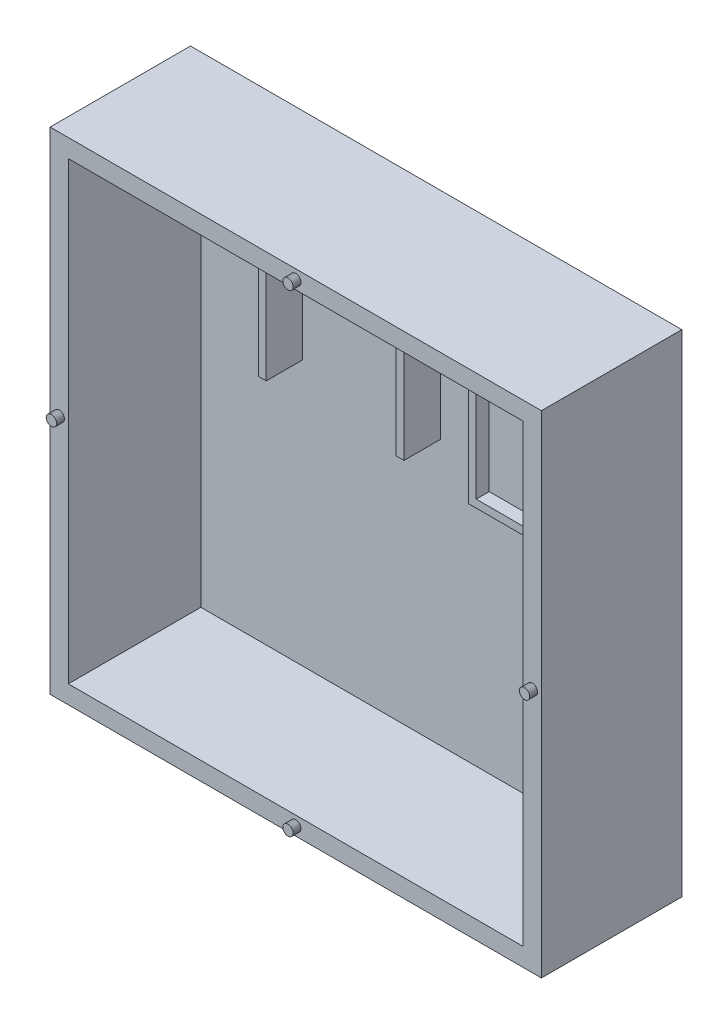
SolidWorks part; units mm, degrees
ref_plane "Front Plane" through (0, 0, 0) normal (0, 0, 1) x (1, 0, 0)
ref_plane "Top Plane" through (0, 0, 0) normal (0, 1, 0) x (1, 0, 0)
ref_plane "Right Plane" through (0, 0, 0) normal (1, 0, 0) x (0, 0, -1)
ref_plane "Plane1" through (0, 0, 0) normal (0, 0, -1) x (-1, 0, 0)
sketch "Sketch1" plane through (0, 0, 0) normal (0, 0, -1) x (-1, 0, 0)
  line L0 (-189, 189) -> (-189, 0)
  line L1 (-189, 0) -> (0, 0)
  line L2 (0, 0) -> (0, 189)
  line L3 (0, 189) -> (-189, 189)
extrude "Boss-Extrude1" add sketch "Sketch1" against normal blind 54
sketch "Sketch2" plane through (0, 0, 54) normal (0, 0, 1) x (1, 0, 0)
  line L0 (3.1527, 96.4696) -> (3.5, 96.5)
  line L1 (3.5, 96.5) -> (3.8473, 96.4696)
  line L2 (3.8473, 96.4696) -> (4.184, 96.3794)
  line L3 (4.184, 96.3794) -> (4.5, 96.232)
  line L4 (4.5, 96.232) -> (4.7856, 96.0321)
  line L5 (4.7856, 96.0321) -> (5.0321, 95.7856)
  line L6 (5.0321, 95.7856) -> (5.2321, 95.5)
  line L7 (5.2321, 95.5) -> (5.3794, 95.184)
  line L8 (5.3794, 95.184) -> (5.4696, 94.8473)
  line L9 (5.4696, 94.8473) -> (5.5, 94.5)
  line L10 (5.5, 94.5) -> (5.4696, 94.1527)
  line L11 (5.4696, 94.1527) -> (5.3794, 93.816)
  line L12 (5.3794, 93.816) -> (5.2321, 93.5)
  line L13 (5.2321, 93.5) -> (5.0321, 93.2144)
  line L14 (5.0321, 93.2144) -> (4.7856, 92.9679)
  line L15 (4.7856, 92.9679) -> (4.5, 92.7679)
  line L16 (4.5, 92.7679) -> (4.184, 92.6206)
  line L17 (4.184, 92.6206) -> (3.8473, 92.5304)
  line L18 (3.8473, 92.5304) -> (3.5, 92.5)
  line L19 (3.5, 92.5) -> (3.1527, 92.5304)
  line L20 (3.1527, 92.5304) -> (2.816, 92.6206)
  line L21 (2.816, 92.6206) -> (2.5, 92.7679)
  line L22 (2.5, 92.7679) -> (2.2144, 92.9679)
  line L23 (2.2144, 92.9679) -> (1.9679, 93.2144)
  line L24 (1.9679, 93.2144) -> (1.7679, 93.5)
  line L25 (1.7679, 93.5) -> (1.6206, 93.816)
  line L26 (1.6206, 93.816) -> (1.5304, 94.1527)
  line L27 (1.5304, 94.1527) -> (1.5, 94.5)
  line L28 (1.5, 94.5) -> (1.5304, 94.8473)
  line L29 (1.5304, 94.8473) -> (1.6206, 95.184)
  line L30 (1.6206, 95.184) -> (1.7679, 95.5)
  line L31 (1.7679, 95.5) -> (1.9679, 95.7856)
  line L32 (1.9679, 95.7856) -> (2.2144, 96.0321)
  line L33 (2.2144, 96.0321) -> (2.5, 96.232)
  line L34 (2.5, 96.232) -> (2.816, 96.3794)
  line L35 (2.816, 96.3794) -> (3.1527, 96.4696)
extrude "Boss-Extrude2" add sketch "Sketch2" along normal blind 3
sketch "Sketch3" plane through (0, 0, 54) normal (0, 0, 1) x (1, 0, 0)
  line L0 (96.0321, 184.2144) -> (95.7856, 183.9679)
  line L1 (95.7856, 183.9679) -> (95.5, 183.7679)
  line L2 (95.5, 183.7679) -> (95.184, 183.6206)
  line L3 (95.184, 183.6206) -> (94.8473, 183.5304)
  line L4 (94.8473, 183.5304) -> (94.5, 183.5)
  line L5 (94.5, 183.5) -> (94.1527, 183.5304)
  line L6 (94.1527, 183.5304) -> (93.816, 183.6206)
  line L7 (93.816, 183.6206) -> (93.5, 183.7679)
  line L8 (93.5, 183.7679) -> (93.2144, 183.9679)
  line L9 (93.2144, 183.9679) -> (92.9679, 184.2144)
  line L10 (92.9679, 184.2144) -> (92.768, 184.5)
  line L11 (92.768, 184.5) -> (92.6206, 184.816)
  line L12 (92.6206, 184.816) -> (92.5304, 185.1527)
  line L13 (92.5304, 185.1527) -> (92.5, 185.5)
  line L14 (92.5, 185.5) -> (92.5304, 185.8473)
  line L15 (92.5304, 185.8473) -> (92.6206, 186.184)
  line L16 (92.6206, 186.184) -> (92.768, 186.5)
  line L17 (92.768, 186.5) -> (92.9679, 186.7856)
  line L18 (92.9679, 186.7856) -> (93.2144, 187.0321)
  line L19 (93.2144, 187.0321) -> (93.5, 187.232)
  line L20 (93.5, 187.232) -> (93.816, 187.3794)
  line L21 (93.816, 187.3794) -> (94.1527, 187.4696)
  line L22 (94.1527, 187.4696) -> (94.5, 187.5)
  line L23 (94.5, 187.5) -> (94.8473, 187.4696)
  line L24 (94.8473, 187.4696) -> (95.184, 187.3794)
  line L25 (95.184, 187.3794) -> (95.5, 187.232)
  line L26 (95.5, 187.232) -> (95.7856, 187.0321)
  line L27 (95.7856, 187.0321) -> (96.0321, 186.7856)
  line L28 (96.0321, 186.7856) -> (96.2321, 186.5)
  line L29 (96.2321, 186.5) -> (96.3794, 186.184)
  line L30 (96.3794, 186.184) -> (96.4696, 185.8473)
  line L31 (96.4696, 185.8473) -> (96.5, 185.5)
  line L32 (96.5, 185.5) -> (96.4696, 185.1527)
  line L33 (96.4696, 185.1527) -> (96.3794, 184.816)
  line L34 (96.3794, 184.816) -> (96.2321, 184.5)
  line L35 (96.2321, 184.5) -> (96.0321, 184.2144)
extrude "Boss-Extrude3" add sketch "Sketch3" along normal blind 3
sketch "Sketch4" plane through (0, 0, 54) normal (0, 0, 1) x (1, 0, 0)
  line L0 (185.8473, 92.5304) -> (185.5, 92.5)
  line L1 (185.5, 92.5) -> (185.1527, 92.5304)
  line L2 (185.1527, 92.5304) -> (184.816, 92.6206)
  line L3 (184.816, 92.6206) -> (184.5, 92.7679)
  line L4 (184.5, 92.7679) -> (184.2144, 92.9679)
  line L5 (184.2144, 92.9679) -> (183.9679, 93.2144)
  line L6 (183.9679, 93.2144) -> (183.768, 93.5)
  line L7 (183.768, 93.5) -> (183.6206, 93.816)
  line L8 (183.6206, 93.816) -> (183.5304, 94.1527)
  line L9 (183.5304, 94.1527) -> (183.5, 94.5)
  line L10 (183.5, 94.5) -> (183.5304, 94.8473)
  line L11 (183.5304, 94.8473) -> (183.6206, 95.184)
  line L12 (183.6206, 95.184) -> (183.768, 95.5)
  line L13 (183.768, 95.5) -> (183.9679, 95.7856)
  line L14 (183.9679, 95.7856) -> (184.2144, 96.0321)
  line L15 (184.2144, 96.0321) -> (184.5, 96.232)
  line L16 (184.5, 96.232) -> (184.816, 96.3794)
  line L17 (184.816, 96.3794) -> (185.1527, 96.4696)
  line L18 (185.1527, 96.4696) -> (185.5, 96.5)
  line L19 (185.5, 96.5) -> (185.8473, 96.4696)
  line L20 (185.8473, 96.4696) -> (186.184, 96.3794)
  line L21 (186.184, 96.3794) -> (186.5, 96.232)
  line L22 (186.5, 96.232) -> (186.7856, 96.0321)
  line L23 (186.7856, 96.0321) -> (187.0321, 95.7856)
  line L24 (187.0321, 95.7856) -> (187.2321, 95.5)
  line L25 (187.2321, 95.5) -> (187.3794, 95.184)
  line L26 (187.3794, 95.184) -> (187.4696, 94.8473)
  line L27 (187.4696, 94.8473) -> (187.5, 94.5)
  line L28 (187.5, 94.5) -> (187.4696, 94.1527)
  line L29 (187.4696, 94.1527) -> (187.3794, 93.816)
  line L30 (187.3794, 93.816) -> (187.2321, 93.5)
  line L31 (187.2321, 93.5) -> (187.0321, 93.2144)
  line L32 (187.0321, 93.2144) -> (186.7856, 92.9679)
  line L33 (186.7856, 92.9679) -> (186.5, 92.7679)
  line L34 (186.5, 92.7679) -> (186.184, 92.6206)
  line L35 (186.184, 92.6206) -> (185.8473, 92.5304)
extrude "Boss-Extrude4" add sketch "Sketch4" along normal blind 3
sketch "Sketch5" plane through (0, 0, 54) normal (0, 0, 1) x (1, 0, 0)
  line L0 (92.9679, 2.2144) -> (92.768, 2.5)
  line L1 (92.768, 2.5) -> (92.6206, 2.816)
  line L2 (92.6206, 2.816) -> (92.5304, 3.1527)
  line L3 (92.5304, 3.1527) -> (92.5, 3.5)
  line L4 (92.5, 3.5) -> (92.5304, 3.8473)
  line L5 (92.5304, 3.8473) -> (92.6206, 4.184)
  line L6 (92.6206, 4.184) -> (92.768, 4.5)
  line L7 (92.768, 4.5) -> (92.9679, 4.7856)
  line L8 (92.9679, 4.7856) -> (93.2144, 5.0321)
  line L9 (93.2144, 5.0321) -> (93.5, 5.2321)
  line L10 (93.5, 5.2321) -> (93.816, 5.3794)
  line L11 (93.816, 5.3794) -> (94.1527, 5.4696)
  line L12 (94.1527, 5.4696) -> (94.5, 5.5)
  line L13 (94.5, 5.5) -> (94.8473, 5.4696)
  line L14 (94.8473, 5.4696) -> (95.184, 5.3794)
  line L15 (95.184, 5.3794) -> (95.5, 5.2321)
  line L16 (95.5, 5.2321) -> (95.7856, 5.0321)
  line L17 (95.7856, 5.0321) -> (96.0321, 4.7856)
  line L18 (96.0321, 4.7856) -> (96.2321, 4.5)
  line L19 (96.2321, 4.5) -> (96.3794, 4.184)
  line L20 (96.3794, 4.184) -> (96.4696, 3.8473)
  line L21 (96.4696, 3.8473) -> (96.5, 3.5)
  line L22 (96.5, 3.5) -> (96.4696, 3.1527)
  line L23 (96.4696, 3.1527) -> (96.3794, 2.816)
  line L24 (96.3794, 2.816) -> (96.2321, 2.5)
  line L25 (96.2321, 2.5) -> (96.0321, 2.2144)
  line L26 (96.0321, 2.2144) -> (95.7856, 1.9679)
  line L27 (95.7856, 1.9679) -> (95.5, 1.7679)
  line L28 (95.5, 1.7679) -> (95.184, 1.6206)
  line L29 (95.184, 1.6206) -> (94.8473, 1.5304)
  line L30 (94.8473, 1.5304) -> (94.5, 1.5)
  line L31 (94.5, 1.5) -> (94.1527, 1.5304)
  line L32 (94.1527, 1.5304) -> (93.816, 1.6206)
  line L33 (93.816, 1.6206) -> (93.5, 1.7679)
  line L34 (93.5, 1.7679) -> (93.2144, 1.9679)
  line L35 (93.2144, 1.9679) -> (92.9679, 2.2144)
extrude "Boss-Extrude5" add sketch "Sketch5" along normal blind 3
sketch "Sketch6" plane through (0, 0, 54) normal (0, 0, 1) x (1, 0, 0)
  line L0 (182, 7) -> (182, 182)
  line L1 (182, 182) -> (7, 182)
  line L2 (7, 182) -> (7, 7)
  line L3 (7, 7) -> (182, 7)
extrude "Cut-Extrude1" cut sketch "Sketch6" against normal blind 51
sketch "Sketch7" plane through (0, 0, 3) normal (0, 0, 1) x (1, 0, 0)
  line L0 (96.1364, 161) -> (46.1364, 161)
  line L1 (46.1364, 161) -> (46.1364, 109)
  line L2 (46.1364, 109) -> (43.1364, 109)
  line L3 (43.1364, 109) -> (43.1364, 164)
  line L4 (43.1364, 164) -> (99.1364, 164)
  line L5 (99.1364, 164) -> (99.1364, 109)
  line L6 (99.1364, 109) -> (96.1364, 109)
  line L7 (96.1364, 109) -> (96.1364, 161)
extrude "Boss-Extrude6" add sketch "Sketch7" along normal blind 14
sketch "Sketch8" plane through (0, 0, 3) normal (0, 0, 1) x (1, 0, 0)
  line L0 (154.928, 98) -> (114.928, 98)
  line L1 (114.928, 98) -> (114.928, 167)
  line L2 (114.928, 167) -> (154.928, 167)
  line L3 (154.928, 167) -> (154.928, 98)
extrude "Boss-Extrude7" add sketch "Sketch8" along normal blind 5
sketch "Sketch9" plane through (0, 0, 8) normal (0, 0, 1) x (1, 0, 0)
  line L0 (151.928, 101) -> (151.928, 164)
  line L1 (151.928, 164) -> (117.928, 164)
  line L2 (117.928, 164) -> (117.928, 101)
  line L3 (117.928, 101) -> (151.928, 101)
extrude "Cut-Extrude2" cut sketch "Sketch9" against normal blind 5
